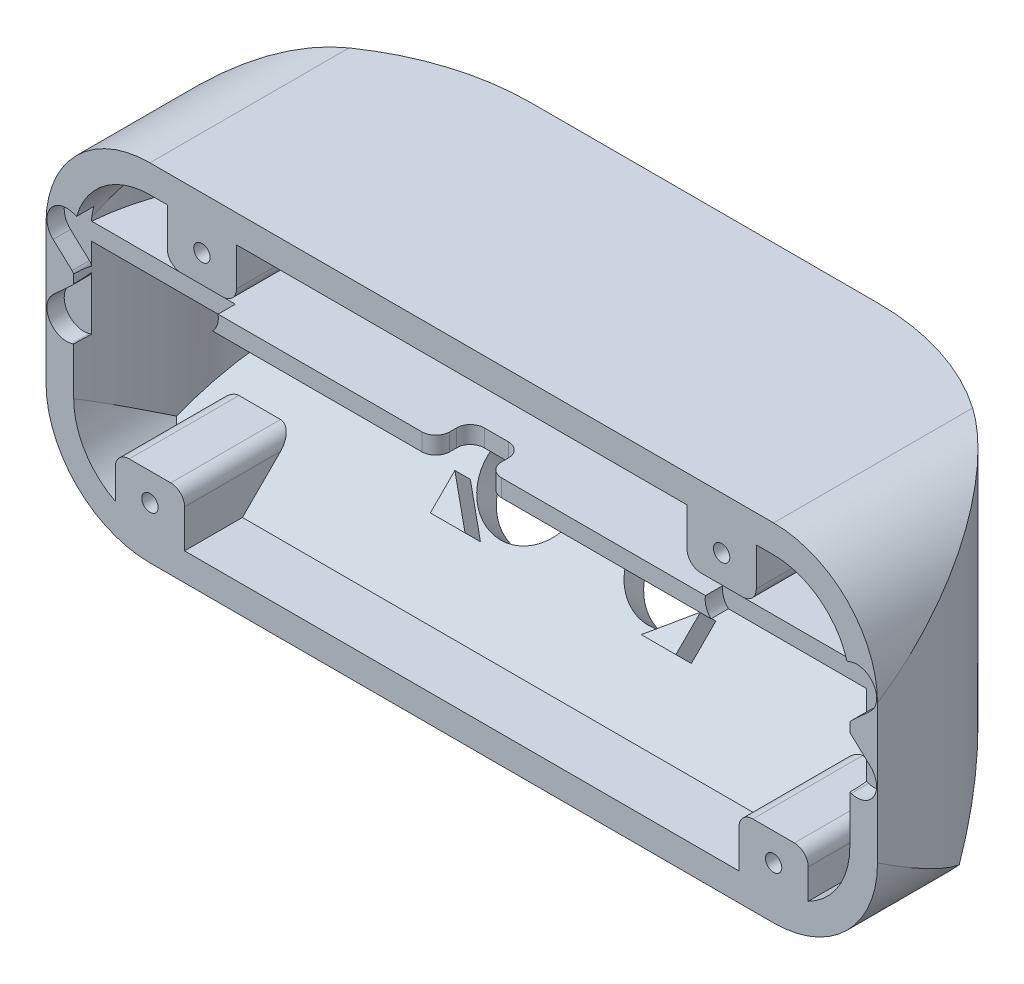
SolidWorks part; units mm, degrees
ref_plane "Front Plane" through (0, 0, 0) normal (0, 0, 1) x (1, 0, 0)
ref_plane "Top Plane" through (0, 0, 0) normal (0, 1, 0) x (1, 0, 0)
ref_plane "Right Plane" through (0, 0, 0) normal (1, 0, 0) x (0, 0, -1)
sketch "Sketch4" plane through (0, 0, 0) normal (0, 1, 0) x (1, 0, 0)
  line L0 (-76.2, 0) -> (76.2, 0)
  line L1 (-31.75, 44.45) -> (31.75, 44.45)
  line L2 (-34.925, 0) -> (34.925, 0) construction
  arc A0 (-76.2, 0) -> (-31.75, 44.45) centre (-31.75, 0) cw
  arc A1 (76.2, 0) -> (31.75, 44.45) centre (31.75, 0) ccw
  point P11 (0, 0)
  dimension "D1" = 63.5
  dimension "D2" = 152.4
extrude "Boss-Extrude2" add sketch "Sketch4" along normal mid plane 63.5
sketch "Sketch2" plane through (0, 0, 0) normal (0, 0, 1) x (1, 0, 0)
  line L0 (-57.15, 31.75) -> (57.15, 31.75)
  line L1 (76.2, 12.7) -> (76.2, -12.7)
  line L2 (57.15, -31.75) -> (-57.15, -31.75)
  line L3 (-76.2, 12.7) -> (-76.2, -12.7)
  line L5 (-76.2, -31.75) -> (76.2, -31.75)
  line L6 (-76.2, -31.75) -> (-76.2, 31.75)
  line L7 (-76.2, 31.75) -> (76.2, 31.75)
  line L8 (76.2, -31.75) -> (76.2, 31.75)
  line L9 (-76.2, -31.75) -> (76.2, 31.75) construction
  line L10 (-76.2, 31.75) -> (76.2, -31.75) construction
  arc A0 (-57.15, 31.75) -> (-76.2, 12.7) centre (-57.15, 12.7) ccw
  arc A1 (-76.2, -12.7) -> (-57.15, -31.75) centre (-57.15, -12.7) ccw
  arc A2 (57.15, -31.75) -> (76.2, -12.7) centre (57.15, -12.7) ccw
  arc A3 (76.2, 12.7) -> (57.15, 31.75) centre (57.15, 12.7) ccw
  point P2 (0, 0)
  point P20 (0, 31.75)
  point P21 (-76.2, 0)
  dimension "D4" = 19.05
  dimension "D1" = 63.5
  dimension "D2" = 152.4
  dimension "D3" = 114.3
extrude "Cut-Extrude2" cut sketch "Sketch2" against normal up to next contours A0 L7 L6 | A1 L6 L5 | A2 L5 L8 | A3 L8 L7
sketch "Sketch5" plane through (0, 0, 0) normal (1, 0, 0) x (0, 0, -1)
  line L1 (44.45, 31.75) -> (44.45, -31.75) construction
  line L4 (0, -31.75) -> (12.7, -31.75) construction
  line L7 (44.45, -31.75) -> (44.45, 0)
  line L8 (36.478, -31.75) -> (0, -31.75) construction
  line L9 (12.7, -31.75) -> (44.45, 0)
  line L10 (44.45, -31.75) -> (12.7, -31.75)
  dimension "D1" = 45
  dimension "D2" = 12.7
extrude "Cut-Extrude3" cut sketch "Sketch5" against normal through all both and the other way through all
shell "Shell2" thickness 5.08
sketch "Sketch7" plane through (0, 0, 0) normal (0, 0, 1) x (1, 0, 0)
  line L0 (-71.12, 12.7) -> (-71.12, -12.7) construction
  line L1 (-71.12, 13.97) -> (71.12, 13.97)
  line L2 (-71.12, 13.97) -> (-71.12, 10.795)
  line L3 (-71.12, 10.795) -> (71.12, 10.795)
  line L4 (71.12, 13.97) -> (71.12, 10.795)
  line L5 (71.12, 12.7) -> (71.12, -12.7) construction
  line L6 (-57.15, 26.67) -> (57.15, 26.67) construction
  dimension "D1" = 12.7
  dimension "D2" = 3.175
extrude "Boss-Extrude3" add sketch "Sketch7" against normal up to next
sketch "Sketch8" plane through (0, 13.97, 0) normal (0, 1, 0) x (1, 0, 0)
  line L0 (-57.15, 0) -> (57.15, 0) construction
  line L1 (-4.7625, 0) -> (4.7625, 0)
  line L2 (-4.7625, 0) -> (-4.7625, 6.35)
  line L3 (-4.7625, 6.35) -> (4.7625, 6.35)
  line L4 (4.7625, 0) -> (4.7625, 6.35)
  point P6 (0, 6.35)
  dimension "D1" = 6.35
  dimension "D2" = 9.525
extrude "Cut-Extrude4" cut sketch "Sketch8" against normal up to next
fillet "Fillet1" radius 2.54 4 edges at (4.7625, 12.3825, 0) (-4.7625, 12.3825, 0) (4.7625, 12.3825, -6.35) (-4.7625, 12.3825, -6.35)
sketch "Sketch9" plane through (0, 27.4973, -71.9473) normal (0, 0.7071, 0.7071) x (1, 0, 0)
  circle A0 centre (-13.5, -58.9841) radius 8.5
  circle A1 centre (13.5, -58.9841) radius 8.5
  dimension "D1" = 17
extrude "Cut-Extrude5" cut sketch "Sketch9" against normal up to surface (5.08 mm away)
sketch "Sketch10" plane through (0, -19.7957, -17.4701) normal (0, 0.7071, 0.7071) x (1, 0, 0)
  line L1 (-22.5, 22.9783) -> (-16.15, 22.9783)
  line L2 (-22.5, 22.9783) -> (22.5, 22.9783) construction
  line L3 (-22.5, 22.9783) -> (-22.5, 16.6283)
  line L4 (-22.5, 22.9783) -> (-22.5, 2.9783) construction
  line L5 (-22.5, 16.6283) -> (-16.15, 22.9783)
  line L6 (-22.5, 9.3283) -> (-22.5, 2.9783)
  line L7 (-22.5, 22.9783) -> (-22.5, 2.9783) construction
  line L8 (-22.5, 2.9783) -> (-16.15, 2.9783)
  line L9 (22.5, 2.9783) -> (-22.5, 2.9783) construction
  line L10 (-16.15, 2.9783) -> (-22.5, 9.3283)
  line L11 (0, -22.8031) -> (0, 26.0919) construction
  line L12 (22.5, 2.9783) -> (16.15, 2.9783)
  line L13 (22.5, 9.3283) -> (22.5, 2.9783)
  line L14 (16.15, 2.9783) -> (22.5, 9.3283)
  line L15 (22.5, 22.9783) -> (22.5, 16.6283)
  line L16 (22.5, 16.6283) -> (16.15, 22.9783)
  line L17 (22.5, 22.9783) -> (16.15, 22.9783)
  dimension "D1" = 6.35
extrude "Boss-Extrude4" add sketch "Sketch10" along normal blind 4
sketch "Sketch11" plane through (0, 0, 0) normal (0, 0, 1) x (1, 0, 0)
  line L0 (-57.15, 26.67) -> (57.15, 26.67) construction
  line L1 (-53.975, 26.67) -> (-41.275, 26.67)
  line L2 (-53.975, 26.67) -> (-53.975, 17.145)
  line L3 (-53.975, 17.145) -> (-41.275, 17.145)
  line L4 (-41.275, 26.67) -> (-41.275, 17.145)
  line L6 (-63.5, -26.67) -> (-50.8, -26.67)
  line L7 (-63.5, -26.67) -> (-63.5, -17.145)
  line L8 (-63.5, -17.145) -> (-50.8, -17.145)
  line L9 (-50.8, -26.67) -> (-50.8, -17.145)
  line L10 (0, -24.4475) -> (0, 24.4475) construction
  line L11 (50.8, -26.67) -> (50.8, -17.145)
  line L12 (63.5, -26.67) -> (50.8, -26.67)
  line L13 (63.5, -26.67) -> (63.5, -17.145)
  line L14 (63.5, -17.145) -> (50.8, -17.145)
  line L15 (41.275, 26.67) -> (41.275, 17.145)
  line L16 (53.975, 17.145) -> (41.275, 17.145)
  line L17 (53.975, 26.67) -> (53.975, 17.145)
  line L18 (53.975, 26.67) -> (41.275, 26.67)
  line L22 (-57.15, -26.67) -> (57.15, -26.67) construction
  circle A0 centre (-57.15, -22.225) radius 1.5
  circle A1 centre (-47.625, 22.225) radius 1.5
  circle A2 centre (57.15, -22.225) radius 1.5
  circle A3 centre (47.625, 22.225) radius 1.5
  point P11 (-47.625, 22.225)
  point P12 (-57.15, -22.225)
  point P14 (-47.625, 26.67)
  point P16 (-57.15, -17.145)
  dimension "D5" = 3
  dimension "D1" = 9.525
  dimension "D2" = 12.7
  dimension "D3" = 9.525
  dimension "D4" = 12.7
extrude "Boss-Extrude5" add sketch "Sketch11" against normal up to next
fillet "Fillet2" radius 2.54 8 edges at (-63.5, -17.145, -10.0604) (-50.8, -17.145, -10.0604) (63.5, -17.145, -10.0604) (50.8, -17.145, -10.0604) (53.975, 17.145, -16.2484) (41.275, 17.145, -19.1002) (-53.975, 17.145, -16.2484) (-41.275, 17.145, -19.1002)
sketch "Sketch13" plane through (0, 0, 0) normal (0, 0, 1) x (1, 0, 0)
  line L5 (71.4238, 7.5156) -> (74.885, 10.716) construction
  line L6 (71.4238, 5.1844) -> (74.885, 1.984) construction
  line L7 (66.8838, -2.6791) -> (71.386, -4.0763) construction
  line L8 (64.865, -3.8446) -> (63.8239, -8.4423) construction
  line L9 (55.785, -3.8446) -> (56.8261, -8.4423) construction
  line L10 (53.7662, -2.6791) -> (49.264, -4.0763) construction
  line L11 (49.2262, 5.1844) -> (45.765, 1.984) construction
  line L12 (49.2262, 7.5156) -> (45.765, 10.716) construction
  line L13 (53.7662, 15.3791) -> (49.264, 16.7763) construction
  line L14 (55.785, 16.5446) -> (56.8261, 21.1423) construction
  line L15 (64.865, 16.5446) -> (63.8239, 21.1423) construction
  line L16 (66.8838, 15.3791) -> (71.386, 16.7763) construction
  line L17 (71.4238, 7.5156) -> (74.885, 10.716)
  line L18 (71.4238, 5.1844) -> (74.885, 1.984)
  line L19 (66.8838, -2.6791) -> (71.386, -4.0763)
  line L20 (64.865, -3.8446) -> (63.8239, -8.4423)
  line L21 (55.785, -3.8446) -> (56.8261, -8.4423)
  line L22 (53.7662, -2.6791) -> (49.264, -4.0763)
  line L23 (49.2262, 5.1844) -> (45.765, 1.984)
  line L24 (49.2262, 7.5156) -> (45.765, 10.716)
  line L25 (53.7662, 15.3791) -> (49.264, 16.7763)
  line L26 (55.785, 16.5446) -> (56.8261, 21.1423)
  line L27 (64.865, 16.5446) -> (63.8239, 21.1423)
  line L28 (66.8838, 15.3791) -> (71.386, 16.7763)
  line L29 (0, -24.4475) -> (0, 24.4475) construction
  line L30 (-66.8838, 15.3791) -> (-71.386, 16.7763)
  line L31 (-64.865, 16.5446) -> (-63.8239, 21.1423)
  line L32 (-55.785, 16.5446) -> (-56.8261, 21.1423)
  line L33 (-53.7662, 15.3791) -> (-49.264, 16.7763)
  line L34 (-49.2262, 7.5156) -> (-45.765, 10.716)
  line L35 (-49.2262, 5.1844) -> (-45.765, 1.984)
  line L36 (-53.7662, -2.6791) -> (-49.264, -4.0763)
  line L37 (-55.785, -3.8446) -> (-56.8261, -8.4423)
  line L38 (-64.865, -3.8446) -> (-63.8239, -8.4423)
  line L39 (-66.8838, -2.6791) -> (-71.386, -4.0763)
  line L40 (-71.4238, 5.1844) -> (-74.885, 1.984)
  line L41 (-71.4238, 7.5156) -> (-74.885, 10.716)
  arc A0 (74.885, 10.716) -> (71.386, 16.7763) centre (72.4494, 13.35) ccw construction
  arc A1 (71.4238, 7.5156) -> (71.4238, 5.1844) centre (72.5016, 6.35) ccw construction
  arc A2 (71.386, -4.0763) -> (74.885, 1.984) centre (72.4494, -0.65) ccw construction
  arc A3 (66.8838, -2.6791) -> (64.865, -3.8446) centre (66.4133, -4.1952) ccw construction
  arc A4 (56.8261, -8.4423) -> (63.8239, -8.4423) centre (60.325, -7.65) ccw construction
  arc A5 (55.785, -3.8446) -> (53.7662, -2.6791) centre (54.2367, -4.1952) ccw construction
  arc A6 (45.765, 1.984) -> (49.264, -4.0763) centre (48.2006, -0.65) ccw construction
  arc A7 (49.2262, 5.1844) -> (49.2262, 7.5156) centre (48.1484, 6.35) ccw construction
  arc A8 (49.264, 16.7763) -> (45.765, 10.716) centre (48.2006, 13.35) ccw construction
  arc A9 (53.7662, 15.3791) -> (55.785, 16.5446) centre (54.2367, 16.8952) ccw construction
  arc A10 (63.8239, 21.1423) -> (56.8261, 21.1423) centre (60.325, 20.35) ccw construction
  arc A11 (64.865, 16.5446) -> (66.8838, 15.3791) centre (66.4133, 16.8952) ccw construction
  arc A12 (74.885, 10.716) -> (71.386, 16.7763) centre (72.4494, 13.35) ccw
  arc A13 (71.4238, 7.5156) -> (71.4238, 5.1844) centre (72.5016, 6.35) ccw
  arc A14 (71.386, -4.0763) -> (74.885, 1.984) centre (72.4494, -0.65) ccw
  arc A15 (66.8838, -2.6791) -> (64.865, -3.8446) centre (66.4133, -4.1952) ccw
  arc A16 (56.8261, -8.4423) -> (63.8239, -8.4423) centre (60.325, -7.65) ccw
  arc A17 (55.785, -3.8446) -> (53.7662, -2.6791) centre (54.2367, -4.1952) ccw
  arc A18 (45.765, 1.984) -> (49.264, -4.0763) centre (48.2006, -0.65) ccw
  arc A19 (49.2262, 5.1844) -> (49.2262, 7.5156) centre (48.1484, 6.35) ccw
  arc A20 (49.264, 16.7763) -> (45.765, 10.716) centre (48.2006, 13.35) ccw
  arc A21 (53.7662, 15.3791) -> (55.785, 16.5446) centre (54.2367, 16.8952) ccw
  arc A22 (63.8239, 21.1423) -> (56.8261, 21.1423) centre (60.325, 20.35) ccw
  arc A23 (64.865, 16.5446) -> (66.8838, 15.3791) centre (66.4133, 16.8952) ccw
  arc A24 (-64.865, 16.5446) -> (-66.8838, 15.3791) centre (-66.4133, 16.8952) cw
  arc A25 (-63.8239, 21.1423) -> (-56.8261, 21.1423) centre (-60.325, 20.35) cw
  arc A26 (-53.7662, 15.3791) -> (-55.785, 16.5446) centre (-54.2367, 16.8952) cw
  arc A27 (-49.264, 16.7763) -> (-45.765, 10.716) centre (-48.2006, 13.35) cw
  arc A28 (-49.2262, 5.1844) -> (-49.2262, 7.5156) centre (-48.1484, 6.35) cw
  arc A29 (-45.765, 1.984) -> (-49.264, -4.0763) centre (-48.2006, -0.65) cw
  arc A30 (-55.785, -3.8446) -> (-53.7662, -2.6791) centre (-54.2367, -4.1952) cw
  arc A31 (-56.8261, -8.4423) -> (-63.8239, -8.4423) centre (-60.325, -7.65) cw
  arc A32 (-66.8838, -2.6791) -> (-64.865, -3.8446) centre (-66.4133, -4.1952) cw
  arc A33 (-71.386, -4.0763) -> (-74.885, 1.984) centre (-72.4494, -0.65) cw
  arc A34 (-71.4238, 7.5156) -> (-71.4238, 5.1844) centre (-72.5016, 6.35) cw
  arc A35 (-74.885, 10.716) -> (-71.386, 16.7763) centre (-72.4494, 13.35) cw
extrude "Cut-Extrude6" cut sketch "Sketch13" against normal blind 3.175
